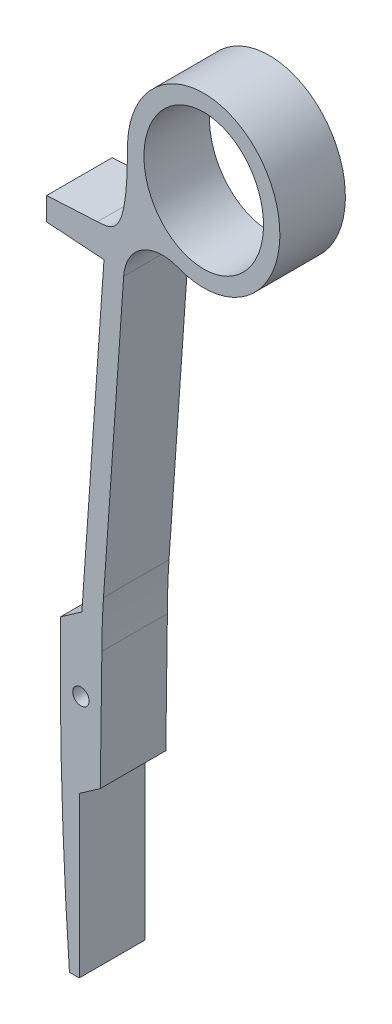
SolidWorks part; units mm, degrees
ref_plane "前视基准面" through (0, 0, 0) normal (0, 0, 1) x (1, 0, 0)
ref_plane "上视基准面" through (0, 0, 0) normal (0, 1, 0) x (1, 0, 0)
ref_plane "右视基准面" through (0, 0, 0) normal (1, 0, 0) x (0, 0, -1)
sketch "草图1" plane through (0, 0, 0) normal (0, 0, 1) x (1, 0, 0)
  line L0 (0, 11.25) -> (0, -37.35) construction
  line L1 (-1.75, -37.35) -> (-0.25, -37.35)
  line L2 (-0.25, -37.35) -> (-0.25, -12.95)
  line L3 (-0.25, -12.95) -> (2.9633, -10.7)
  line L4 (2.9633, -10.7) -> (3.2022, 7.55)
  line L5 (3.2022, 7.55) -> (0.15, 11.25)
  line L7 (3.2022, 7.55) -> (0.15, 11.25)
  line L8 (0.15, 11.25) -> (-3.1266, 8.9557)
  arc A0 (-3.1266, 8.9557) -> (-1.75, -37.35) centre (581.8448, 3.1728) ccw
  circle A1 centre (0, 0) radius 1.25
  point P12 (0, 0)
  point P13 (0, 0)
  point P14 (0, 0)
  dimension "D12" = 585
  dimension "D13" = 2.5
  dimension "D1" = 37.35
  dimension "D2" = 11.25
  dimension "D3" = 0.25
  dimension "D4" = 1.5
  dimension "D5" = 125
  dimension "D6" = 2.25
  dimension "D7" = 24.4
  dimension "D8" = 0.15
  dimension "D10" = 18.25
  dimension "D11" = 125.75
  dimension "D14" = 4
sketch "草图3" plane through (0, 0, 0) normal (0, 0, 1) x (1, 0, 0)
  ellipse E0 centre (18.75, 76.25) end of major axis (18.75, 65.875) minor radius 9.125
  point P7 (18.75, 63.375)
  dimension "D1" = 20.75
  dimension "D2" = 18.25
  dimension "D3" = 76.25
  dimension "D4" = 18.75
  dimension "D5" = 2.5
sketch "草图4" plane through (0, 0, 0) normal (0, 0, 1) x (1, 0, 0)
  line L0 (0.15, 11.25) -> (3.524, 59.5)
  line L1 (0.15, 11.25) -> (-3.1266, 8.9557) construction
  line L2 (3.524, 59.5) -> (-5.226, 60.1119)
  line L3 (-5.226, 60.1119) -> (-5.226, 63.6119)
  line L4 (-5.226, 63.6119) -> (2.524, 64.018)
  line L5 (18.75, 65.875) -> (14.8857, 64.106) construction
  line L6 (7.125, 71.0225) -> (7.125, 81.4775) construction
  line L7 (3.4493, 14.8) -> (6.5261, 58.8)
  line L8 (14.8857, 64.106) -> (9.8857, 66.0475) construction
  line L9 (0.15, 11.25) -> (3.2022, 7.55)
  arc A0 (3.4493, 14.8) -> (3.2022, 7.55) centre (104.7021, 7.7197) ccw
  ellipse E1 centre (18.75, 76.25) end of major axis (18.75, 63.3737) minor radius 11.625 (14.8857, 64.106) -> (7.125, 76.25) ccw
  ellipse E2 centre (18.75, 76.25) end of major axis (18.75, 65.875) minor radius 9.125
  spline S0 degree 3 poles (14.0536, 64.0891) (18.75, 63.0179) (23.4464, 64.0891) (27.3073, 67.0437) (29.8018, 71.3124) (30.6616, 76.25) (29.8018, 81.1876) (27.3073, 85.4563) (23.4464, 88.4109) (18.75, 89.4821) (14.0536, 88.4109) (10.1927, 85.4563) (7.6982, 81.1876) (6.8384, 76.25) (7.6982, 71.3124) (10.1927, 67.0437) (14.0536, 64.0891) (18.75, 63.0179) (23.4464, 64.0891) knots -1.178097 -0.785398 -0.392699 0 0.392699 0.785398 1.178097 1.570796 1.963495 2.356194 2.748894 3.141593 3.534292 3.926991 4.31969 4.712389 5.105088 5.497787 5.890486 6.283185 6.675884 7.068583 7.461283 only from (18.75, 63.375) to (18.75, 63.375) construction
  spline S1 degree 3 poles (7.125, 76.25) (7.125, 64.25) (5.187, 64.1576) (2.524, 64.018) knots 0 0 0 0 1 1 1 1
  spline S3 degree 3 poles (6.5261, 58.8) (6.8284, 63.1228) (10.8462, 65.6745) (14.8857, 64.106) knots 0 0 0 0 1 1 1 1
  point P12 (7.125, 76.25)
  point P18 (3.4493, 14.8)
  dimension "D8" = 36
  dimension "D9" = 8
  dimension "D11" = 101.5
  dimension "D13" = 13
  dimension "D15" = 13
  dimension "D1" = 129
  dimension "D2" = 48.25
  dimension "D3" = 3.5
  dimension "D4" = 93
  dimension "D5" = 7.75
  dimension "D6" = 8.75
  dimension "D7" = 4.25
  dimension "D10" = 7.25
  dimension "D12" = 44
  dimension "D14" = 5
extrude "凸台-拉伸1" add sketch "草图4" along normal mid plane 10
extrude "凸台-拉伸2" add sketch "草图1" along normal mid plane 10 contours A1 | L5 L8 A0 L1 L2 L3 L4
sketch "草图6" plane through (0, 0, 0) normal (1, 0, 0) x (0, 0, -1)
  line L0 (0, -39) -> (0, 91) construction
  point P3 (-2.7849, 0)
  point P4 (-1.928, 32.1178)
  point P5 (-1.2853, 76.462)
  point P6 (-1.2853, 91)
  point P7 (-2.7849, 0)
  point P8 (0, 0)
  point P9 (0, 0)
  point P10 (-2.7849, 0)
  point P11 (0, 0)
  dimension "D1" = 130
  dimension "D2" = 39
